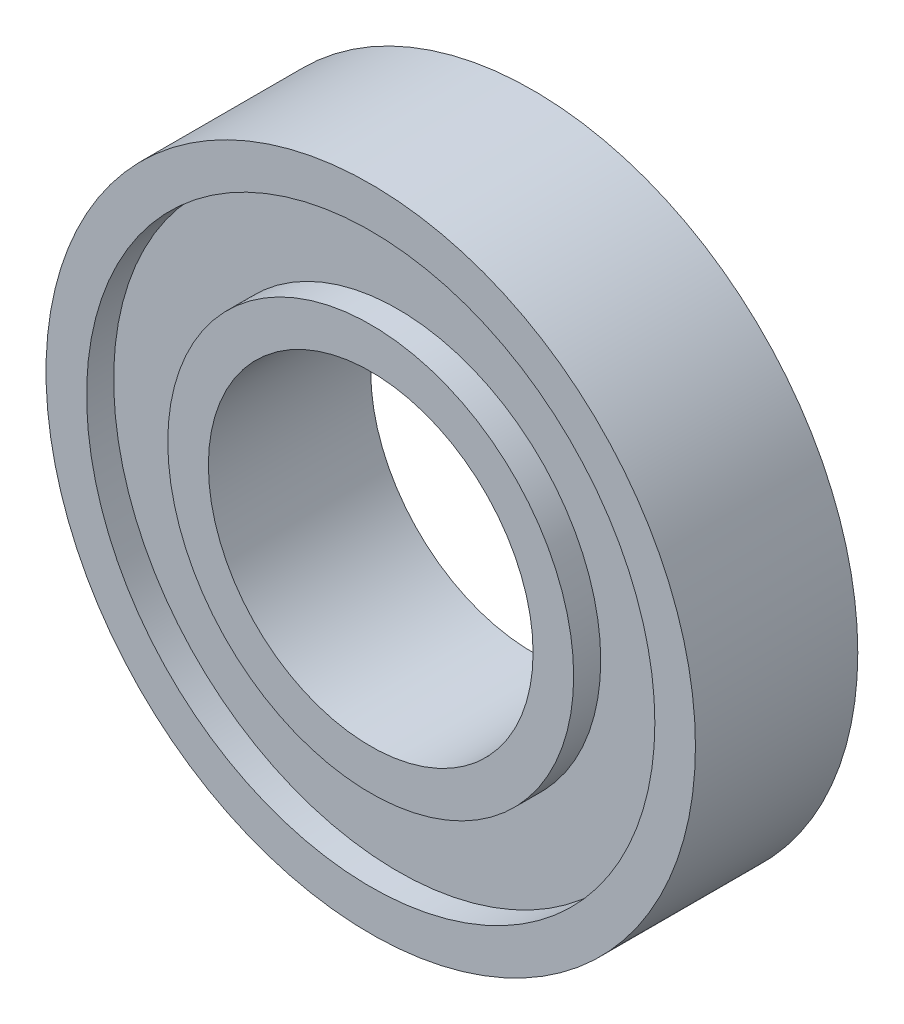
SolidWorks part; units mm, degrees
ref_plane "前视基准面" through (0, 0, 0) normal (0, 0, 1) x (1, 0, 0)
ref_plane "上视基准面" through (0, 0, 0) normal (0, 1, 0) x (1, 0, 0)
ref_plane "右视基准面" through (0, 0, 0) normal (1, 0, 0) x (0, 0, -1)
sketch "草图1" plane through (0, 0, 0) normal (0, 0, 1) x (1, 0, 0)
  circle A0 centre (0, 0) radius 6
  circle A1 centre (0, 0) radius 3
  dimension "D1" = 12
  dimension "D2" = 6
extrude "凸台-拉伸1" add sketch "草图1" along normal mid plane 3
sketch "草图2" plane through (0, 0, 1.5) normal (0, 0, 1) x (1, 0, 0)
  circle A0 centre (0, 0) radius 3.75
  circle A1 centre (0, 0) radius 5.25
  dimension "D1" = 7.5
  dimension "D2" = 10.5
extrude "切除-拉伸1" cut sketch "草图2" against normal blind 0.5
mirror "镜向1" about plane through (0, 0, 0) normal (0, 0, 1) of "切除-拉伸1"
